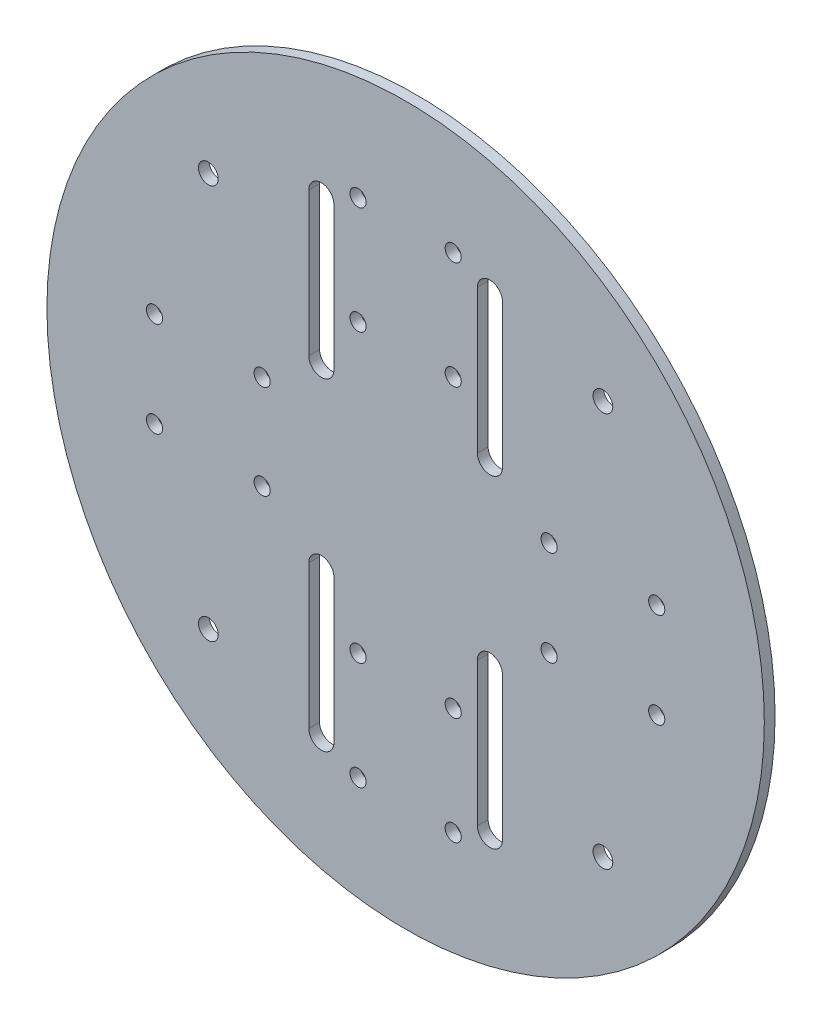
SolidWorks part; units mm, degrees
ref_plane "Ön Düzlem" through (0, 0, 0) normal (0, 0, 1) x (1, 0, 0)
ref_plane "Üst Düzlem" through (0, 0, 0) normal (0, 1, 0) x (1, 0, 0)
ref_plane "Sağ Düzlem" through (0, 0, 0) normal (1, 0, 0) x (0, 0, -1)
sketch "Çizim1" plane through (0, 0, 0) normal (0, 0, 1) x (1, 0, 0)
  circle A0 centre (0, 0) radius 100
  dimension "D1" = 200
extrude "Yükseklik-Ekstrüzyon1" add sketch "Çizim1" along normal blind 30
sketch "Çizim9" plane through (0, 0, 30) normal (0, 0, 1) x (1, 0, 0)
  line L0 (23.5, 65) -> (23.5, 25) construction
  line L1 (27, 65) -> (27, 25)
  line L2 (20, 65) -> (20, 25)
  line L3 (-23.5, 65) -> (-23.5, 25) construction
  line L4 (-20, 65) -> (-20, 25)
  line L5 (-27, 65) -> (-27, 25)
  line L6 (-23.5, -25) -> (-23.5, -65) construction
  line L7 (-20, -25) -> (-20, -65)
  line L8 (-27, -25) -> (-27, -65)
  line L9 (23.5, -65) -> (23.5, -25) construction
  line L10 (20, -65) -> (20, -25)
  line L11 (27, -65) -> (27, -25)
  arc A0 (27, 65) -> (20, 65) centre (23.5, 65) ccw
  arc A1 (20, 25) -> (27, 25) centre (23.5, 25) ccw
  arc A2 (-20, 65) -> (-27, 65) centre (-23.5, 65) ccw
  arc A3 (-27, 25) -> (-20, 25) centre (-23.5, 25) ccw
  arc A4 (-20, -25) -> (-27, -25) centre (-23.5, -25) ccw
  arc A5 (-27, -65) -> (-20, -65) centre (-23.5, -65) ccw
  arc A6 (20, -65) -> (27, -65) centre (23.5, -65) ccw
  arc A7 (27, -25) -> (20, -25) centre (23.5, -25) ccw
  circle A8 centre (0, -55) radius 2.6 construction
  circle A9 centre (0, 0) radius 100 construction
  point P2 (23.5, 45)
  point P8 (-23.5, 45)
  point P15 (-23.5, -45)
  point P22 (23.5, -45)
  dimension "D2" = 40
  dimension "D11" = 50
  dimension "D13" = 65
  dimension "D1" = 7
  dimension "D3" = 40
  dimension "D4" = 7
  dimension "D5" = 7
  dimension "D6" = 40
  dimension "D7" = 40
  dimension "D8" = 7
  dimension "D9" = 40
  dimension "D10" = 50
  dimension "D12" = 20
  dimension "D14" = 65
extrude "Kes-Ekstrüzyon1" cut sketch "Çizim9" against normal through all
hole_wizard "M5 Boşluklu Delik2" positions "Çizim19" profile "Çizim18" hole size "M5" standard "ANSI Metrik" end condition through all
sketch "Çizim19" plane through (0, 0, 30) normal (0, 0, 1) x (1, 0, 0)
  point P0 (-55, 55)
  point P2 (55, 55)
  point P4 (55, -55)
  point P6 (-55, -55)
sketch "Çizim18" plane through (-55, 55, 30) normal (1, 0, 0) x (0, -1, 0)
  line L0 (0, 0) -> (0, 30)
  line L1 (0, 30) -> (2.75, 30)
  line L2 (2.75, 30) -> (2.75, 0)
  line L5 (2.75, 0) -> (0, 0)
  line L11 (0, -6.35) -> (0, 107.95) construction
  dimension "Thru Hole Dia." = 5.5
  dimension "Thru Hole Depth" = 30
sketch "Çizim20" plane through (0, 0, 30) normal (0, 0, 1) x (1, 0, 0)
  circle A0 centre (0, 8.4795) radius 183.5376
extrude "Kes-Ekstrüzyon2" cut sketch "Çizim20" against normal blind 27
hole_wizard "M4 Boşluklu Delik1" positions "Çizim23" profile "Çizim22" hole size "M4" standard "ANSI Metrik" end condition through all
sketch "Çizim23" plane through (0, 0, 3) normal (0, 0, 1) x (1, 0, 0)
  point P0 (-13.265, 40)
  point P2 (-13.265, 70)
  point P4 (13.265, 70)
  point P6 (13.265, 40)
  dimension "D1" = 26.53
  dimension "D2" = 30
  dimension "D3" = 26.53
  dimension "D4" = 30
  dimension "D5" = 40
  dimension "D6" = 13.265
sketch "Çizim22" plane through (-13.265, 40, 3) normal (1, 0, 0) x (0, -1, 0)
  line L0 (0, 0) -> (0, 3)
  line L1 (0, 3) -> (2.25, 3)
  line L2 (2.25, 3) -> (2.25, 0)
  line L5 (2.25, 0) -> (0, 0)
  line L11 (0, -6.35) -> (0, 107.95) construction
  dimension "Thru Hole Dia." = 4.5
  dimension "Thru Hole Depth" = 3
hole_wizard "M4 Boşluklu Delik2" positions "Çizim25" profile "Çizim24" hole size "M4" standard "ANSI Metrik" end condition through all
sketch "Çizim25" plane through (0, 0, 3) normal (0, 0, 1) x (1, 0, 0)
  point P0 (40, 13.265)
  point P2 (70, 13.265)
  point P4 (70, -13.265)
  point P6 (40, -13.265)
  point P8 (-40, -12.9968)
  point P10 (-40, 13.265)
  point P12 (-70, 13.5332)
  point P14 (-70, -12.9968)
  point P16 (-13.265, -40)
  point P18 (13.265, -40)
  point P20 (13.265, -70)
  point P22 (-13.265, -70)
  dimension "D1" = 30
  dimension "D2" = 30
  dimension "D3" = 26.53
  dimension "D4" = 26.53
  dimension "D5" = 40
  dimension "D6" = 13.265
  dimension "D7" = 30
  dimension "D8" = 30
  dimension "D9" = 26.53
  dimension "D10" = 26.53
  dimension "D11" = 40
  dimension "D12" = 13.265
  dimension "D13" = 30
  dimension "D14" = 30
  dimension "D15" = 26.53
  dimension "D16" = 40
  dimension "D17" = 13.265
sketch "Çizim24" plane through (40, 13.265, 3) normal (1, 0, 0) x (0, -1, 0)
  line L0 (0, 0) -> (0, 3)
  line L1 (0, 3) -> (2.25, 3)
  line L2 (2.25, 3) -> (2.25, 0)
  line L5 (2.25, 0) -> (0, 0)
  line L11 (0, -6.35) -> (0, 107.95) construction
  dimension "Thru Hole Dia." = 4.5
  dimension "Thru Hole Depth" = 3
